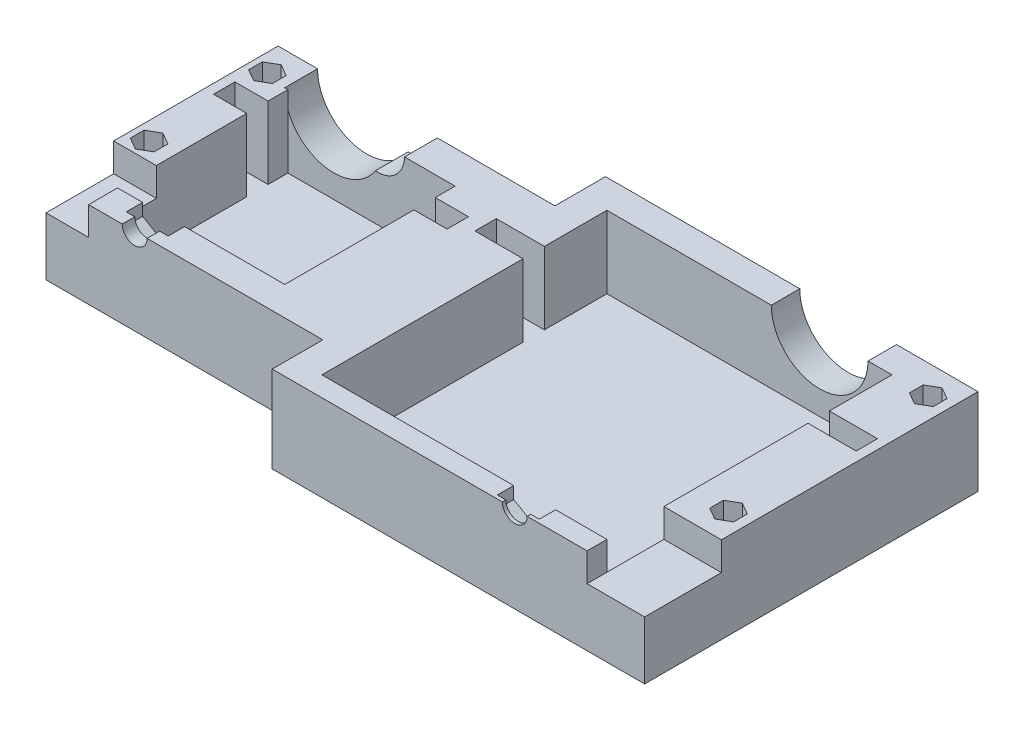
SolidWorks part; units mm, degrees
material "PLA"
ref_plane "Front Plane" through (0, 0, 0) normal (0, 0, 1) x (1, 0, 0)
ref_plane "Top Plane" through (0, 0, 0) normal (0, 1, 0) x (1, 0, 0)
ref_plane "Right Plane" through (0, 0, 0) normal (1, 0, 0) x (0, 0, -1)
sketch "Sketch1" plane through (0, 0, 0) normal (0, 1, 0) x (1, 0, 0)
  line L0 (-26.2, 16.325) -> (-26.2, 23.45)
  line L1 (-26.2, -23.45) -> (26.2, -23.45)
  line L2 (-26.2, -23.45) -> (-26.2, -16.325)
  line L3 (-26.2, 23.45) -> (26.2, 23.45)
  line L4 (26.2, -23.45) -> (26.2, 23.45)
  line L5 (-26.2, -23.45) -> (26.2, 23.45) construction
  line L6 (-26.2, 23.45) -> (26.2, -23.45) construction
  line L7 (-26.2, 16.325) -> (-65.145, 16.325)
  line L9 (-26.2, -16.325) -> (-65.145, -16.325)
  line L10 (-65.145, 16.325) -> (-65.145, -16.325)
  point P0 (0, 0)
  dimension "D1" = 52.4
  dimension "D2" = 46.9
  dimension "D3" = 38.945
  dimension "D4" = 32.65
  dimension "D5" = 7.125
extrude "Boss-Extrude1" add sketch "Sketch1" along normal blind 12.17
sketch "Sketch2" plane through (0, 12.17, 0) normal (0, 1, 0) x (1, 0, 0)
  line L1 (26.2, -23.45) -> (18.1, -23.45)
  line L2 (26.2, -23.45) -> (26.2, -12.65)
  line L3 (26.2, -12.65) -> (18.1, -12.65)
  line L4 (18.1, -23.45) -> (18.1, -12.65)
  line L5 (-65.145, -16.325) -> (-59.145, -16.325)
  line L6 (-65.145, -16.325) -> (-65.145, -6.801)
  line L7 (-65.145, -6.801) -> (-59.145, -6.801)
  line L8 (-59.145, -16.325) -> (-59.145, -6.801)
  dimension "D1" = 9.524
  dimension "D2" = 6
  dimension "D3" = 10.8
  dimension "D4" = 8.1
extrude "Cut-Extrude1" cut sketch "Sketch2" against normal blind 4
sketch "Sketch3" plane through (0, 12.17, 0) normal (0, 1, 0) x (1, 0, 0)
  line L0 (18.1, -23.45) -> (18.1, -20.656) construction
  line L1 (-59.145, -16.325) -> (-26.2, -16.325) construction
  line L2 (18.1, -12.65) -> (18.1, -23.45) construction
  line L12 (-59.145, -16.325) -> (-59.145, -6.801) construction
  line L14 (-59.145, -12.255) -> (-35.625, -12.255)
  line L16 (-59.145, 11.705) -> (-35.625, 11.705)
  line L17 (-35.625, -12.255) -> (-35.625, 5.909)
  line L18 (-59.145, 5.909) -> (-63.81, 5.909)
  line L19 (-63.81, 5.909) -> (-63.81, 8.919)
  line L20 (-63.81, 8.919) -> (-59.145, 8.919)
  line L21 (-47.385, 11.705) -> (-47.385, -12.255) construction
  line L22 (-59.145, 8.919) -> (-59.145, 11.705)
  line L23 (-30.96, 8.919) -> (-35.625, 8.919)
  line L24 (-30.96, 5.909) -> (-30.96, 8.919)
  line L25 (-35.625, 5.909) -> (-30.96, 5.909)
  line L26 (-35.625, 8.919) -> (-35.625, 11.705)
  line L27 (-22, 19.444) -> (-22, 10.644) construction
  line L28 (18.1, -20.656) -> (-22, -20.656)
  line L29 (18.1, -20.656) -> (18.1, 7.644)
  line L30 (18.1, 19.444) -> (-22, 19.444)
  line L31 (-22, -20.656) -> (-22, 7.644)
  line L32 (-22, 10.644) -> (-28.765, 10.644)
  line L33 (-28.765, 10.644) -> (-28.765, 7.644)
  line L34 (-28.765, 7.644) -> (-22, 7.644)
  line L35 (-1.95, 19.444) -> (-1.95, -20.656) construction
  line L36 (24.865, 7.644) -> (18.1, 7.644)
  line L37 (24.865, 10.644) -> (24.865, 7.644)
  line L38 (18.1, 10.644) -> (24.865, 10.644)
  line L39 (-22, 10.644) -> (-22, 19.444)
  line L40 (18.1, 10.644) -> (18.1, 19.444)
  line L42 (-59.145, -12.255) -> (-59.145, 5.909)
  dimension "D1" = 23.96
  dimension "D2" = 23.52
  dimension "D3" = 3.01
  dimension "D4" = 40.1
  dimension "D5" = 40.1
  dimension "D6" = 6.765
  dimension "D7" = 3
  dimension "D8" = 18.164
  dimension "D9" = 4.07
extrude "Cut-Extrude2" cut sketch "Sketch3" against normal blind 10.17
sketch "Sketch4" plane through (0, 0, -23.45) normal (0, 0, -1) x (-1, 0, 0)
  line L0 (-26.2, 12.17) -> (-14.73, 12.17) construction
  line L1 (-26.2, 12.17) -> (26.2, 12.17) construction
  line L2 (-14.73, 12.17) -> (-1.13, 12.17)
  arc A0 (-1.13, 12.17) -> (-14.73, 12.17) centre (-7.93, 12.17) cw
  line M6 (26.2, 12.17) -> (-26.2, 12.17)
  dimension "D1" = 11.47
  dimension "D2" = 13.6
extrude "Cut-Extrude3" cut sketch "Sketch4" against normal up to surface (4.006 mm away) contours A0 M6 up to face at (-1.95, 7.085, -19.444)
sketch "Sketch5" plane through (0, 0, -16.325) normal (0, 0, -1) x (-1, 0, 0)
  line L0 (65.145, 12.17) -> (59.595, 12.17) construction
  line L1 (26.2, 12.17) -> (65.145, 12.17) construction
  line L2 (59.595, 12.17) -> (46.8381, 12.17)
  line L4 (46.8381, 12.17) -> (42.745, 12.17) construction
  line L5 (46.8381, 8.4362) -> (52.0236, 8.4362) construction
  line L6 (52.0236, 8.4362) -> (52.0236, 5.2757) construction
  line L7 (46.8381, 8.4362) -> (42.745, 8.4362) construction
  line L8 (42.745, 8.4362) -> (42.745, 12.1705) construction
  line L9 (42.745, 12.17) -> (46.8381, 12.17)
  arc A2 (46.8381, 8.4362) -> (59.595, 12.17) centre (52.67, 12.1705) ccw
  arc A3 (42.745, 12.1705) -> (46.8381, 8.4362) centre (46.495, 12.1705) ccw
  line M11 (65.145, 12.17) -> (26.2, 12.17)
  dimension "D1" = 5.55
  dimension "D2" = 12.7569
  dimension "D3" = 3.7338
  dimension "D4" = 4.0931
  dimension "D5" = 5.1855
  dimension "D6" = 3.1605
extrude "Cut-Extrude4" cut sketch "Sketch5" against normal up to surface (4.62 mm away) contours A3 A2 M11 up to face at (-47.385, 7.085, -11.705)
sketch "Sketch6" plane through (0, 12.17, 0) normal (0, 1, 0) x (1, 0, 0)
  line L0 (26.2, 23.45) -> (23.2, 23.45) construction
  line L1 (26.2, 23.45) -> (14.73, 23.45) construction
  line L2 (23.2, 23.45) -> (23.2, 21.3841) construction
  line L3 (23.2, 21.3841) -> (23.2, 17.5159) construction
  line L4 (23.2, 17.5159) -> (23.2, -6.7159) construction
  line L5 (23.2, -6.7159) -> (23.2, -10.5841) construction
  line L6 (-65.145, 16.325) -> (-62.645, 16.325) construction
  line L7 (-59.595, 16.325) -> (-65.145, 16.325) construction
  line L8 (-62.645, 16.325) -> (-62.645, 14.2591) construction
  line L9 (-62.645, 14.2591) -> (-62.645, 10.3909) construction
  line L10 (-62.645, 10.3909) -> (-62.645, -2.3909) construction
  line L11 (-62.645, -2.3909) -> (-62.645, -6.2591) construction
  line L13 (-62.645, 14.2591) -> (-64.32, 13.2921)
  line L14 (-64.32, 13.2921) -> (-64.32, 11.3579)
  line L15 (-64.32, 11.3579) -> (-62.645, 10.3909)
  line L16 (-62.645, 10.3909) -> (-60.97, 11.3579)
  line L17 (-60.97, 11.3579) -> (-60.97, 13.2921)
  line L18 (-60.97, 13.2921) -> (-62.645, 14.2591)
  line L19 (-62.645, -2.3909) -> (-64.32, -3.3579)
  line L20 (-64.32, -3.3579) -> (-64.32, -5.2921)
  line L21 (-64.32, -5.2921) -> (-62.645, -6.2591)
  line L22 (-62.645, -6.2591) -> (-60.97, -5.2921)
  line L23 (-60.97, -5.2921) -> (-60.97, -3.3579)
  line L24 (-60.97, -3.3579) -> (-62.645, -2.3909)
  line L25 (23.2, 21.3841) -> (21.525, 20.4171)
  line L26 (21.525, 20.4171) -> (21.525, 18.4829)
  line L27 (21.525, 18.4829) -> (23.2, 17.5159)
  line L28 (23.2, 17.5159) -> (24.875, 18.4829)
  line L29 (24.875, 18.4829) -> (24.875, 20.4171)
  line L30 (24.875, 20.4171) -> (23.2, 21.3841)
  line L31 (23.2, -6.7159) -> (21.525, -7.6829)
  line L32 (21.525, -7.6829) -> (21.525, -9.6171)
  line L33 (21.525, -9.6171) -> (23.2, -10.5841)
  line L34 (23.2, -10.5841) -> (24.875, -9.6171)
  line L35 (24.875, -9.6171) -> (24.875, -7.6829)
  line L36 (24.875, -7.6829) -> (23.2, -6.7159)
  circle A0 centre (-62.645, 12.325) radius 1.675 construction
  circle A1 centre (-62.645, -4.325) radius 1.675 construction
  circle A2 centre (23.2, 19.45) radius 1.675 construction
  circle A3 centre (23.2, -8.65) radius 1.675 construction
  dimension "D1" = 3
  dimension "D2" = 3.8682
  dimension "D3" = 2.0659
  dimension "D4" = 24.2318
  dimension "D5" = 3.8682
  dimension "D6" = 2.5
  dimension "D7" = 2.0659
  dimension "D8" = 3.8682
  dimension "D9" = 12.7818
  dimension "D10" = 3.8682
extrude "Cut-Extrude5" cut sketch "Sketch6" against normal blind 5.25
sketch "Sketch7" plane through (0, 0, 23.45) normal (0, 0, 1) x (1, 0, 0)
  line L0 (26.2, 8.17) -> (26.2, 12.17) construction
  line L1 (26.2, 12.17) -> (9.68, 12.17) construction
  line L2 (-26.2, 12.17) -> (18.1, 12.17) construction
  line L3 (-65.145, 8.17) -> (-65.145, 12.17) construction
  line L4 (-65.145, 12.17) -> (-54.42, 12.17) construction
  line L5 (-59.145, 12.17) -> (-26.2, 12.17) construction
  line L6 (-54.42, 12.17) -> (-50.92, 12.17) construction
  line L7 (9.68, 12.17) -> (6.18, 12.17) construction
  circle A0 centre (-52.67, 12.17) radius 1.75
  circle A1 centre (7.93, 12.17) radius 1.75
  dimension "D1" = 10.725
  dimension "D2" = 3.5
  dimension "D3" = 3.5
  dimension "D4" = 16.52
extrude "Cut-Extrude6" cut sketch "Sketch7" against normal up to surface (11.195 mm away) up to face at (-49.737, 7.302, 12.255)
sketch "Sketch8" plane through (0, 0, 20.656) normal (0, 0, -1) x (-1, 0, 0)
  line L0 (-18.1, 12.17) -> (-10.88, 12.17) construction
  line L1 (-10.88, 12.17) -> (-10.88, 10.4668)
  line L2 (-10.88, 10.4668) -> (-7.93, 8.7636)
  line L3 (-7.93, 8.7636) -> (-4.98, 10.4668)
  line L4 (-4.98, 10.4668) -> (-4.98, 12.17)
  line L5 (22, 12.17) -> (-6.18, 12.17) construction
  line L6 (-9.68, 12.17) -> (-18.1, 12.17) construction
  line L7 (-10.88, 12.17) -> (-4.98, 12.17)
  line L8 (-7.93, 12.17) -> (-7.93, 6.003) construction
  point P13 (0, 0)
  dimension "D1" = 7.22
  dimension "D2" = 5.9
  dimension "D3" = 1.7032
  dimension "D4" = 1.7032
  dimension "D5" = 3.4064
extrude "Cut-Extrude7" cut sketch "Sketch8" against normal blind 2.3
sketch "Sketch9" plane through (0, 0, 12.255) normal (0, 0, -1) x (-1, 0, 0)
  line L0 (59.145, 12.17) -> (55.62, 12.17) construction
  line L1 (59.145, 12.17) -> (54.42, 12.17) construction
  line L2 (42.5, 12.17) -> (49.72, 12.17) construction
  line L3 (49.72, 12.17) -> (49.72, 10.4668)
  line L4 (49.72, 10.4668) -> (52.67, 8.7636)
  line L5 (52.67, 8.7636) -> (55.62, 10.4668)
  line L6 (55.62, 10.4668) -> (55.62, 12.17)
  line L7 (49.72, 12.17) -> (55.62, 12.17)
  line L8 (52.67, 12.17) -> (52.67, 6.003) construction
  point P13 (0, 0)
  dimension "D1" = 7.22
  dimension "D2" = 5.9
  dimension "D3" = 1.7032
  dimension "D4" = 1.7032
  dimension "D5" = 3.4064
  dimension "D6" = 3.525
extrude "Cut-Extrude8" cut sketch "Sketch9" against normal blind 2.3
sketch "Sketch10" plane through (0, 12.17, 0) normal (0, 1, 0) x (1, 0, 0)
  circle A0 centre (-62.645, 12.325) radius 1.25
  circle A1 centre (-62.645, -4.325) radius 1.25
  circle A2 centre (23.2, -8.65) radius 1.25
  circle A3 centre (23.2, 19.45) radius 1.25
  dimension "D1" = 2.5
  dimension "D2" = 2.5
  dimension "D3" = 2.5
  dimension "D4" = 2.5
extrude "Cut-Extrude9" cut sketch "Sketch10" against normal through all
